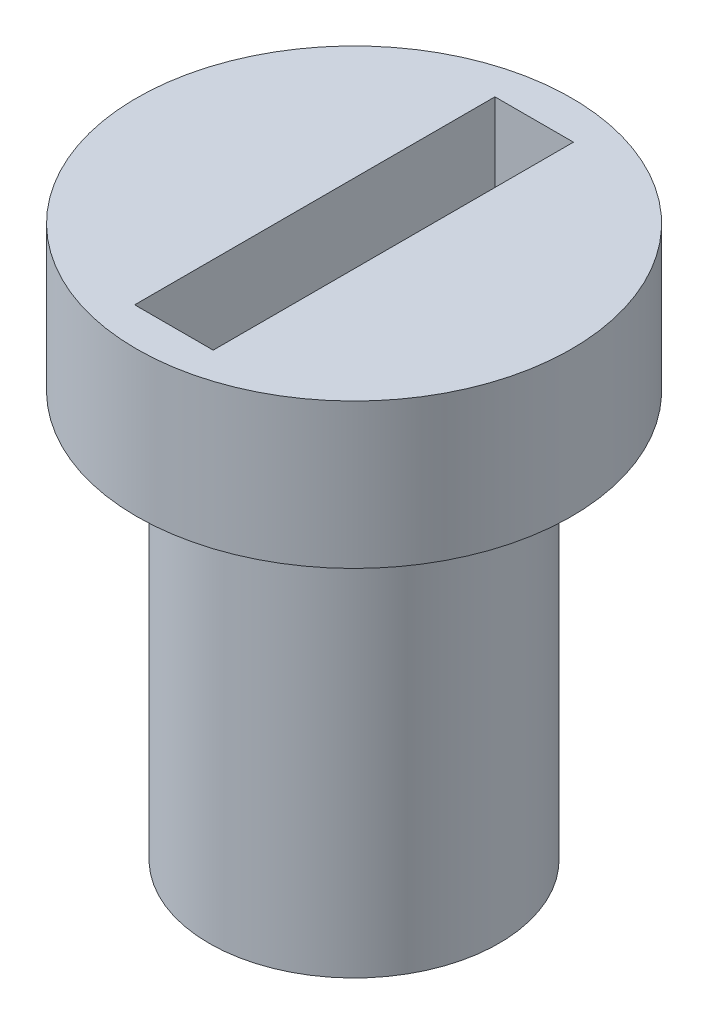
SolidWorks part; units mm, degrees
ref_plane "前视基准面" through (0, 0, 0) normal (0, 0, 1) x (1, 0, 0)
ref_plane "上视基准面" through (0, 0, 0) normal (0, 1, 0) x (1, 0, 0)
ref_plane "右视基准面" through (0, 0, 0) normal (1, 0, 0) x (0, 0, -1)
other "Configuration Table"
sketch "草图1" plane through (0, 0, 0) normal (0, 1, 0) x (1, 0, 0)
  circle A0 centre (0, 0) radius 7.5
  dimension "D1" = 15
extrude "凸台-拉伸1" add sketch "草图1" along normal blind 5
ref_plane "基准面1" through (0, 0, 0) normal (0, -1, 0) x (-1, 0, 0)
sketch "草图2" plane through (0, 0, 0) normal (0, -1, 0) x (-1, 0, 0)
  circle A0 centre (0, 0) radius 5
  dimension "D1" = 10
extrude "凸台-拉伸2" add sketch "草图2" along normal blind 14
cosmetic thread "装饰螺纹线1" parameters "D2"=9
ref_plane "基准面2" through (0, 5, 0) normal (0, 1, 0) x (1, 0, 0)
sketch "草图3" plane through (0, 5, 0) normal (0, 1, 0) x (1, 0, 0)
  line L0 (0, 0) -> (0, 5.6766) construction
  line L5 (0, 0) -> (7.8422, 0) construction
  line L6 (-1.3541, 6.2123) -> (1.3541, 6.2123)
  line L7 (-1.3541, 6.2123) -> (-1.3541, -6.2123)
  line L8 (-1.3541, -6.2123) -> (1.3541, -6.2123)
  line L9 (1.3541, 6.2123) -> (1.3541, -6.2123)
extrude "切除-拉伸1" cut sketch "草图3" against normal blind 3 and the other way through all
